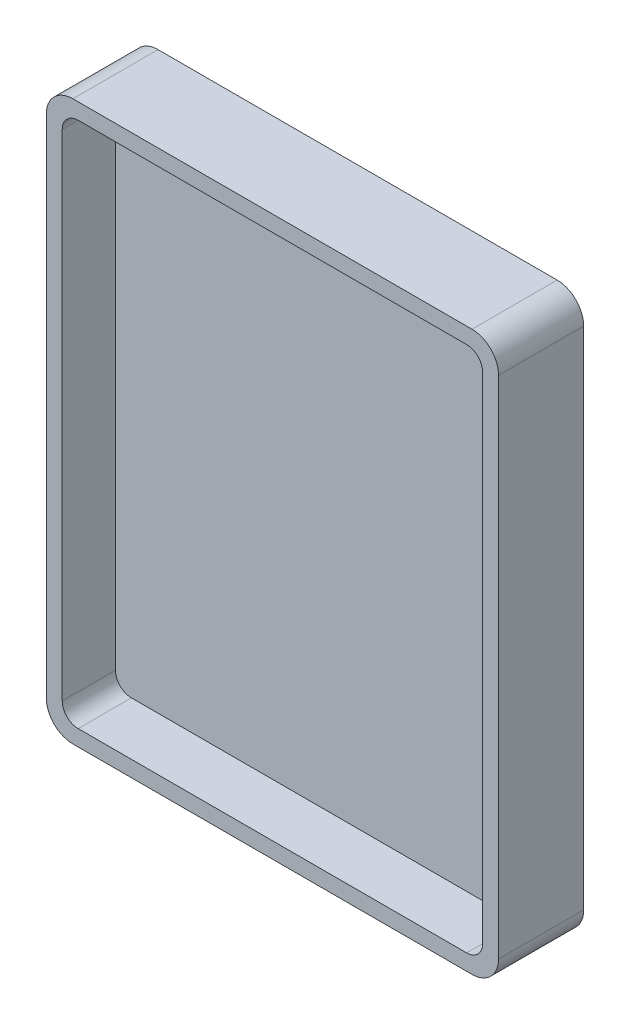
SolidWorks part; units mm, degrees
ref_plane "Front Plane" through (0, 0, 0) normal (0, 0, 1) x (1, 0, 0)
ref_plane "Top Plane" through (0, 0, 0) normal (0, 1, 0) x (1, 0, 0)
ref_plane "Right Plane" through (0, 0, 0) normal (1, 0, 0) x (0, 0, -1)
sketch "Sketch1" plane through (0, 0, 0) normal (0, 0, 1) x (1, 0, 0)
  line L1 (-55, 65) -> (30, 65)
  line L2 (-55, 65) -> (-55, -40)
  line L3 (-55, -40) -> (30, -40)
  line L4 (30, 65) -> (30, -40)
  dimension "D1" = 55
  dimension "D2" = 85
  dimension "D3" = 65
  dimension "D4" = 105
extrude "Boss-Extrude1" add sketch "Sketch1" along normal blind 16
sketch "Sketch2" plane through (0, 0, 16) normal (0, 0, 1) x (1, 0, 0)
  line L0 (30, 65) -> (-55, 65) construction
  line L1 (-52, 62) -> (27, 62)
  line L2 (-52, 62) -> (-52, -37)
  line L3 (-52, -37) -> (27, -37)
  line L4 (27, 62) -> (27, -37)
  line L5 (30, -40) -> (30, 65) construction
  line L6 (-55, -40) -> (30, -40) construction
  line L7 (-55, 65) -> (-55, -40) construction
  dimension "D1" = 3
  dimension "D2" = 3
  dimension "D3" = 3
  dimension "D4" = 3
extrude "Cut-Extrude1" cut sketch "Sketch2" against normal blind 10
fillet "Fillet1" radius 5 4 edges at (30, -40, 8) (30, 65, 8) (-55, 65, 8) (-55, -40, 8)
sketch "Sketch3" plane through (0, 0, 0) normal (0, 0, -1) x (-1, 0, 0)
  line L0 (50, -40) -> (-25, -40) construction
  line L5 (-25, 65) -> (50, 65) construction
  line L9 (55, 60) -> (55, -35) construction
  line L11 (-30, -35) -> (-30, 60) construction
  circle A0 centre (48.5, 58.5) radius 2
  circle A1 centre (-23.5, -33.5) radius 2
  dimension "D3" = 4
  dimension "D4" = 4
  dimension "D5" = 6.5
  dimension "D6" = 6.5
  dimension "D2" = 6.5
  dimension "D1" = 6.5
extrude "Cut-Extrude2" cut sketch "Sketch3" against normal blind 1.5
sketch "Sketch4" plane through (0, 0, 1.5) normal (0, 0, -1) x (-1, 0, 0)
  circle A0 centre (48.5, 58.5) radius 1.35
  circle A1 centre (48.5, 58.5) radius 2 construction
  circle A2 centre (-23.5, -33.5) radius 1.35
  circle A3 centre (-23.5, -33.5) radius 2 construction
  dimension "D1" = 2.7
  dimension "D2" = 2.7
extrude "Cut-Extrude3" cut sketch "Sketch4" against normal through all
fillet "Fillet2" radius 3 4 edges at (27, 62, 11) (27, -37, 11) (-52, -37, 11) (-52, 62, 11)
